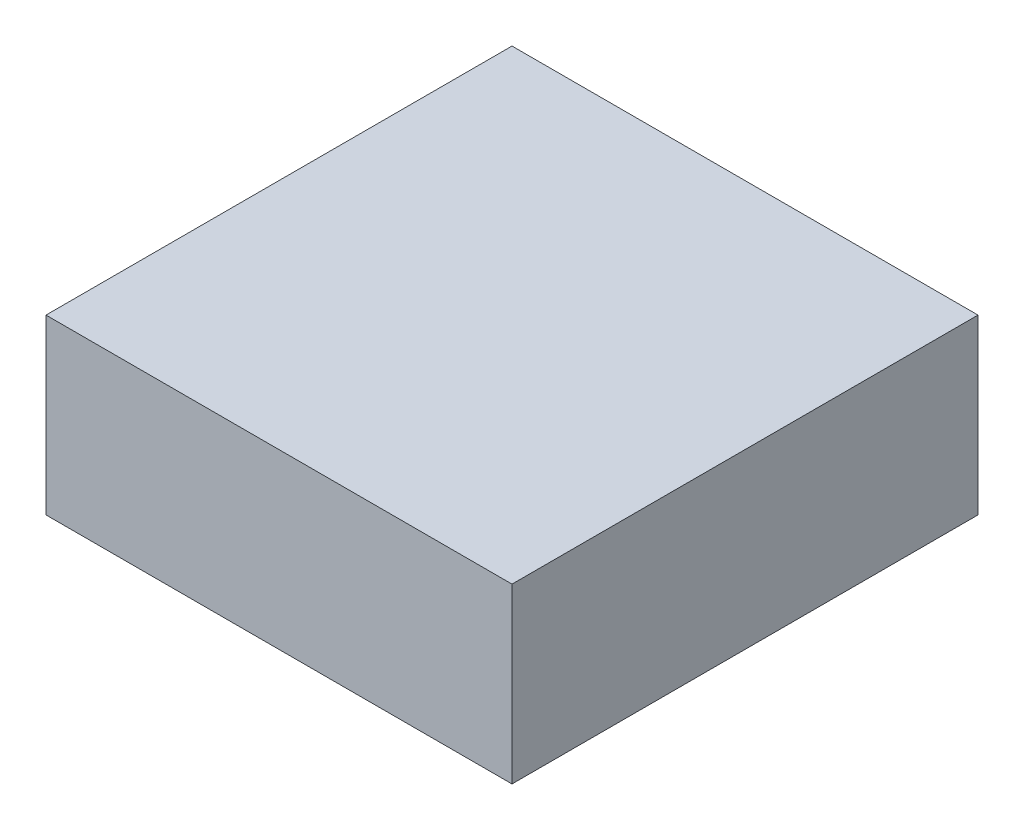
SolidWorks part; units mm, degrees
ref_plane "Front Plane" through (0, 0, 0) normal (0, 0, 1) x (1, 0, 0)
ref_plane "Top Plane" through (0, 0, 0) normal (0, 1, 0) x (1, 0, 0)
ref_plane "Right Plane" through (0, 0, 0) normal (1, 0, 0) x (0, 0, -1)
sketch "Sketch2" plane through (0, 0, 0) normal (0, 1, 0) x (1, 0, 0)
  line L1 (35, -35) -> (-35, -35)
  line L2 (35, -35) -> (35, 35)
  line L3 (35, 35) -> (-35, 35)
  line L4 (-35, -35) -> (-35, 35)
  line L5 (35, -35) -> (-35, 35) construction
  line L6 (35, 35) -> (-35, -35) construction
  point P0 (0, 0)
extrude "Boss-Extrude1" add sketch "Sketch2" along normal blind 26
